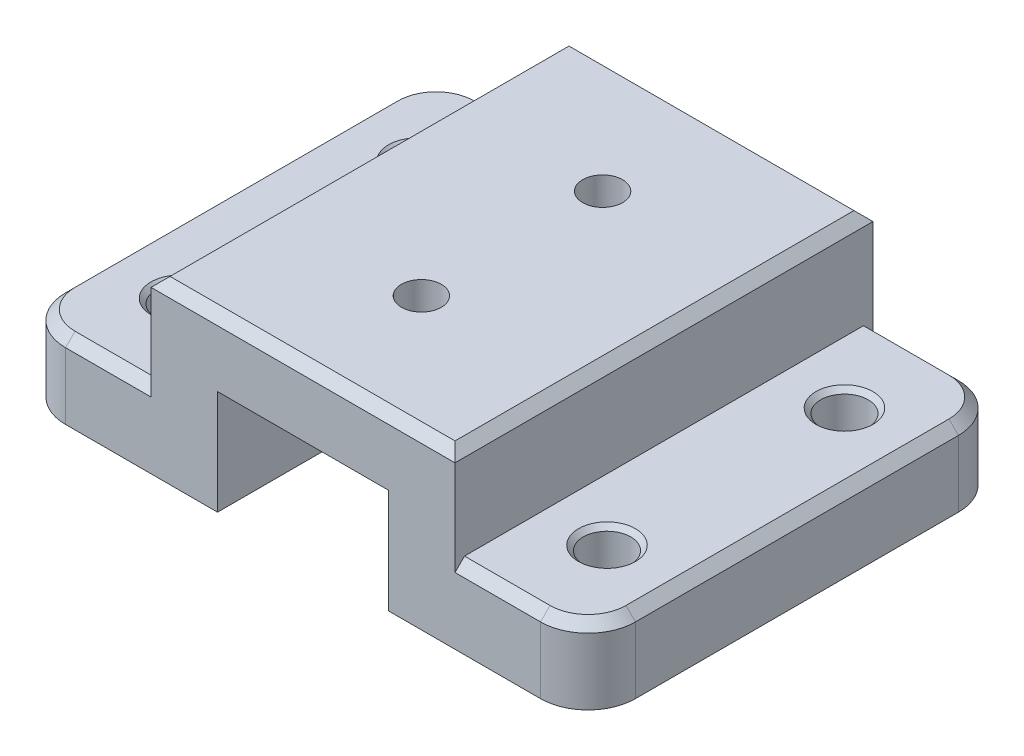
SolidWorks part; units mm, degrees
material "AISI 1010 钢，热轧条材"
ref_plane "前视基准面" through (0, 0, 0) normal (0, 0, 1) x (1, 0, 0)
ref_plane "上视基准面" through (0, 0, 0) normal (0, 1, 0) x (1, 0, 0)
ref_plane "右视基准面" through (0, 0, 0) normal (1, 0, 0) x (0, 0, -1)
sketch "草图1" plane through (0, 0, 0) normal (0, 0, 1) x (1, 0, 0)
  line L9 (-9, 0) -> (-30, 0)
  line L10 (-30, 0) -> (-30, 8)
  line L11 (-30, 8) -> (-16, 8)
  line L12 (-16, 8) -> (-16, 18)
  line L13 (-16, 18) -> (16, 18)
  line L14 (0, 18) -> (0, 11) construction
  line L15 (9, 11) -> (-9, 11)
  line L16 (-9, 11) -> (-9, 0)
  line L17 (9, 11) -> (9, 0)
  line L18 (16, 8) -> (16, 18)
  line L19 (30, 8) -> (16, 8)
  line L20 (30, 0) -> (30, 8)
  line L21 (9, 0) -> (30, 0)
  dimension "D1" = 60
  dimension "D2" = 18
  dimension "D3" = 11
  dimension "D4" = 18
  dimension "D5" = 14
  dimension "D6" = 8
extrude "凸台-拉伸1" add sketch "草图1" against normal mid plane 44
fillet "圆角1" radius 5 4 edges at (-30, 4, -22) (30, 4, -22) (30, 4, 22) (-30, 4, 22)
chamfer "倒角1" distance 1 angle 45 14 edges at (-20.5, 8, -22) (-28.5355, 8, -20.5355) (-30, 8, 0) (-28.5355, 8, 20.5355) (-20.5, 8, 22) (20.5, 8, -22) (28.5355, 8, -20.5355) (30, 8, 0) (28.5355, 8, 20.5355) (20.5, 8, 22) (0, 18, -22) (-16, 18, 0) (0, 18, 22) (16, 18, 0)
sketch "草图4" plane through (0, 8, 0) normal (0, 1, 0) x (1, 0, 0)
  line L0 (30, 17) -> (30, -17) construction
  line L1 (16, 22) -> (25, 22) construction
  circle A0 centre (22.5, 12.5) radius 2.5
  dimension "D1" = 5
  dimension "D2" = 7.5
  dimension "D3" = 9.5
extrude "切除-拉伸1" cut sketch "草图4" against normal through all
mirror "镜向3" about plane through (0, 0, 0) normal (1, 0, 0) of "切除-拉伸1"
mirror "镜向4" about plane through (0, 0, 0) normal (0, 0, 1) of "镜向3", "切除-拉伸1"
chamfer "倒角2" distance 0.5 angle 45 4 edges at (20, 8, -12.5) (20, 8, 12.5) (-20, 8, 12.5) (-20, 8, -12.5)
hole_wizard "M5 螺纹孔1" positions "3D草图2" profile "草图5" tap size "M5" standard "GB" end condition through all
sketch3d "3D草图2"
  line L3 (0, 0, 0) -> (0, 18, 0) construction
  line L5 (0, 18, 0) -> (0, 18, -22.0772) construction
  line L7 (-16, 17, -22) -> (16, 17, -22) construction
  point P0 (0, 18, -9.5401)
  dimension "D1" = 12.5
sketch "草图5" plane through (0, 18, -9.5401) normal (1, 0, 0) x (0, 0, 1)
  line L0 (0, 0) -> (0, 18)
  line L1 (0, 18) -> (2.1, 18)
  line L2 (2.1, 18) -> (2.1, 0)
  line L5 (2.1, 0) -> (0, 0)
  line L11 (0, -6.35) -> (0, 107.95) construction
  dimension "通孔螺纹孔钻头直径" = 4.2
  dimension "通孔螺纹孔钻头深度" = 18
cosmetic thread "孔螺蚊线1" parameters "D2"=5
mirror "镜向5" about plane through (0, 0, 0) normal (0, 0, 1) of "M5 螺纹孔1"
cosmetic thread "孔螺蚊线2" parameters "D2"=5
